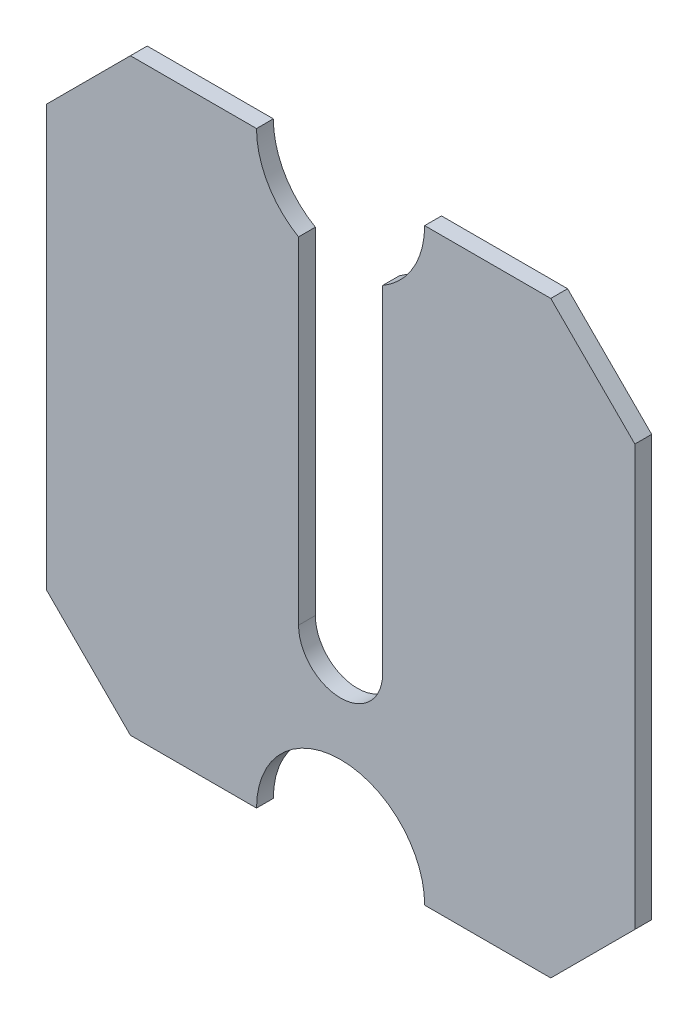
SolidWorks part; units mm, degrees
ref_plane "Front Plane" through (0, 0, 0) normal (0, 0, 1) x (1, 0, 0)
ref_plane "Top Plane" through (0, 0, 0) normal (0, 1, 0) x (1, 0, 0)
ref_plane "Right Plane" through (0, 0, 0) normal (1, 0, 0) x (0, 0, -1)
sketch "Sketch1" plane through (0, 0, 0) normal (0, 0, 1) x (1, 0, 0)
  line L0 (-25.4125, 374.5875) -> (-100.4125, 374.5875)
  line L1 (-275.4125, 24.5875) -> (-200.4125, 24.5875)
  line L2 (-325.4125, 74.5875) -> (-325.4125, 324.5875)
  line L3 (-150.4125, 199.5875) -> (-150.4125, 156.2863) construction
  line L4 (24.5875, 74.5875) -> (24.5875, 324.5875)
  line L5 (-325.4125, 199.5875) -> (24.5875, 199.5875) construction
  line L6 (-150.4125, 106.2863) -> (-150.4125, 74.5875) construction
  line L7 (-275.4125, 374.5875) -> (-275.4125, 24.5875) construction
  line L8 (-175.4125, 331.2863) -> (-175.4125, 131.2863)
  line L9 (-325.4125, 324.5875) -> (-175.4125, 324.5875) construction
  line L10 (-25.4125, 374.5875) -> (-25.4125, 24.5875) construction
  line L11 (-325.4125, 74.5875) -> (24.5875, 74.5875) construction
  line L12 (-275.4125, 374.5875) -> (-325.4125, 324.5875)
  line L13 (-25.4125, 374.5875) -> (24.5875, 324.5875)
  line L14 (-25.4125, 24.5875) -> (24.5875, 74.5875)
  line L15 (-275.4125, 24.5875) -> (-325.4125, 74.5875)
  line L16 (-100.4125, 24.5875) -> (-25.4125, 24.5875)
  line L17 (-200.4125, 374.5875) -> (-275.4125, 374.5875)
  line L18 (-125.4125, 331.2863) -> (-125.4125, 131.2863)
  line L19 (-125.4125, 324.5875) -> (24.5875, 324.5875) construction
  arc A0 (-200.4125, 374.5875) -> (-175.4125, 331.2863) centre (-150.4125, 374.5875) ccw
  arc A1 (-100.4125, 24.5875) -> (-200.4125, 24.5875) centre (-150.4125, 24.5875) ccw
  arc A2 (-175.4125, 131.2863) -> (-125.4125, 131.2863) centre (-150.4125, 131.2863) ccw
  arc A3 (-125.4125, 331.2863) -> (-100.4125, 374.5875) centre (-150.4125, 374.5875) ccw
  point P21 (-150.4125, 324.5875)
extrude "Boss-Extrude1" add sketch "Sketch1" along normal blind 10
ref_plane "Plane1" through (0, 0, 5) normal (0, 0, 1) x (1, 0, 0)
sketch "Sketch2" plane through (0, 0, 5) normal (0, 0, 1) x (1, 0, 0)
  line L0 (-150.4125, 24.5875) -> (-150.4125, 374.5875) construction
